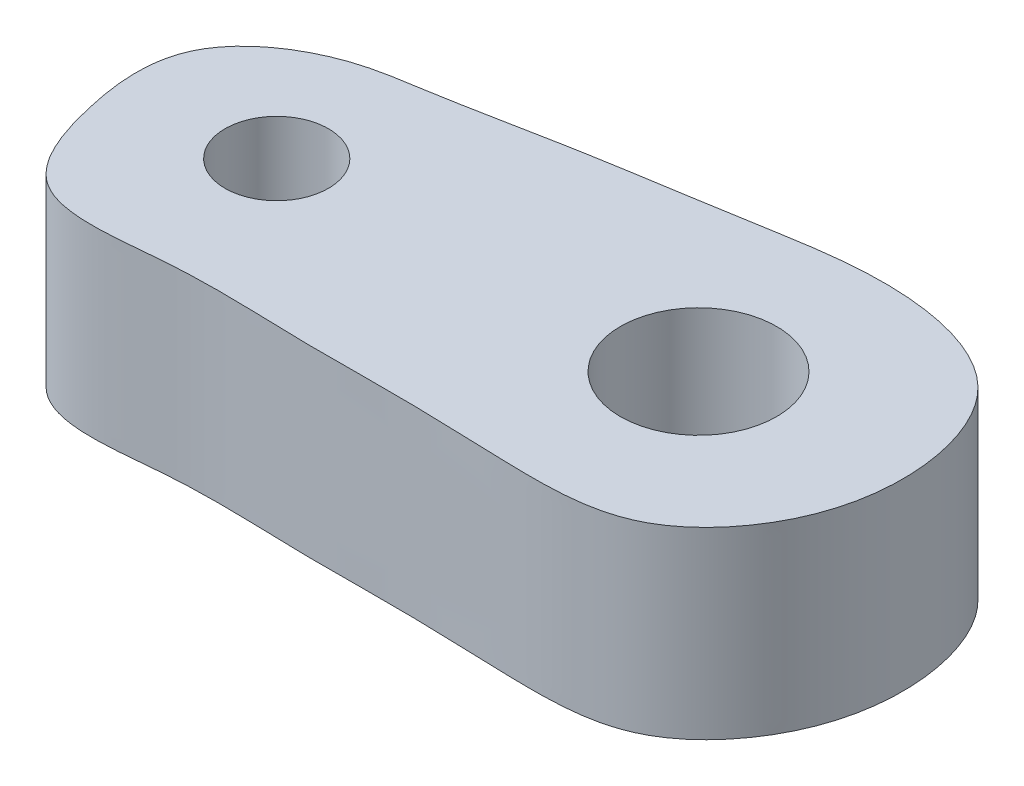
SolidWorks part; units mm, degrees
ref_plane "Front Plane" through (0, 0, 0) normal (0, 0, 1) x (1, 0, 0)
ref_plane "Top Plane" through (0, 0, 0) normal (0, 1, 0) x (1, 0, 0)
ref_plane "Right Plane" through (0, 0, 0) normal (1, 0, 0) x (0, 0, -1)
sketch "Sketch1" plane through (0, 0, 0) normal (0, 1, 0) x (1, 0, 0)
  line L0 (47.2297, 219.0186) -> (732.563, 219.0186) construction
  circle A0 centre (-15.7935, 65.7585) radius 1.7
  circle A1 centre (-24.393, 65.1838) radius 1.125
  spline S0 degree 3 poles (-25.7279, 67.841) (-23.6023, 68.1423) (-21.1965, 68.6571) (-18.2941, 69.0803) (-15.3513, 69.6454) (-12.1899, 69.0276) (-11.2985, 66.0398) (-11.9244, 63.7027) (-13.6399, 61.966) (-16.0246, 61.9296) (-18.3215, 62.0515) (-20.9272, 61.9875) (-23.4522, 62.1641) (-26.5782, 61.5986) (-27.4967, 64.136) (-27.7316, 66.564) (-25.7279, 67.841) (-23.6023, 68.1423) (-21.1965, 68.6571) knots -0.150725 -0.094309 -0.030541 0 0.069347 0.153622 0.219475 0.299218 0.363564 0.427286 0.475903 0.534683 0.596775 0.652194 0.727563 0.798163 0.849275 0.905691 0.969459 1 1.069347 1.153622 1.219475 only from (-24.1056, 68.0797) to (-24.1056, 68.0797)
extrude "Boss-Extrude4" add sketch "Sketch1" along normal blind 4
